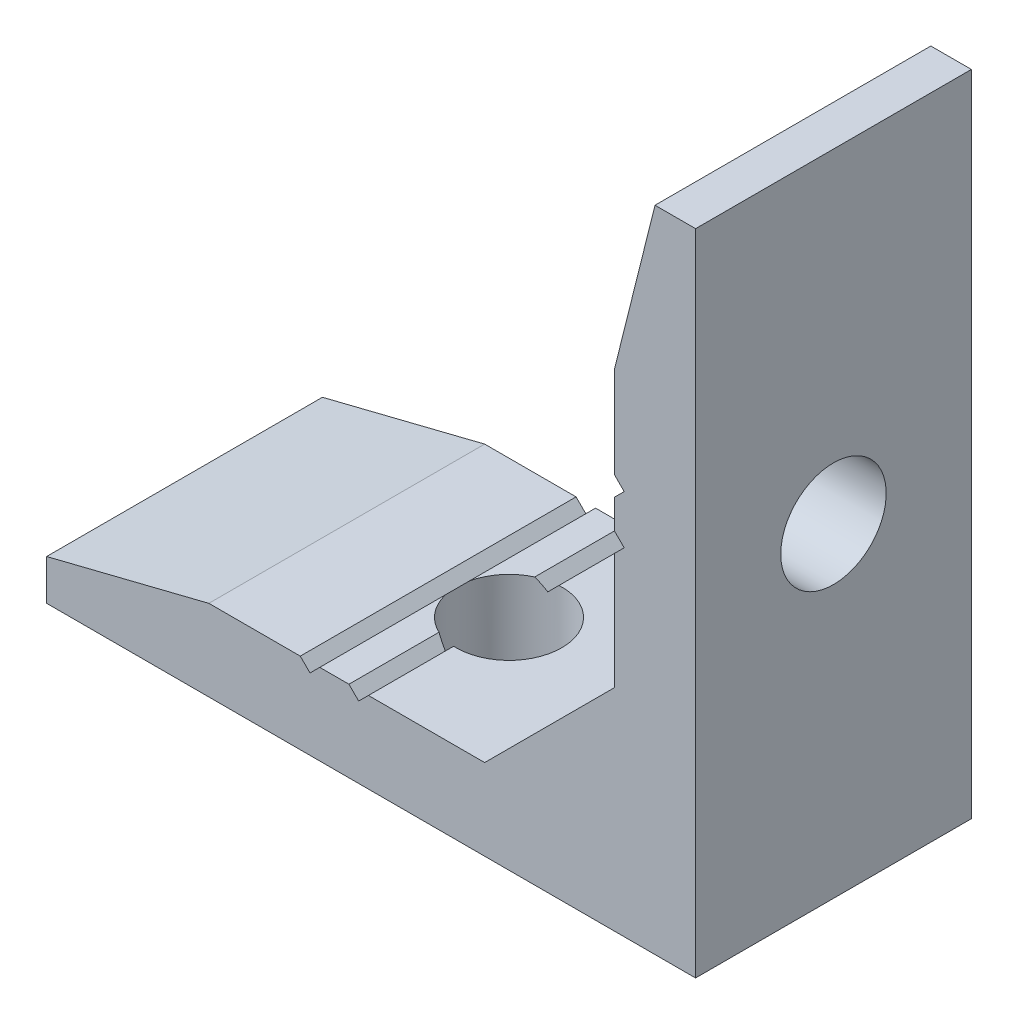
SolidWorks part; units mm, degrees
ref_plane "前视基准面" through (0, 0, 0) normal (0, 0, 1) x (1, 0, 0)
ref_plane "上视基准面" through (0, 0, 0) normal (0, 1, 0) x (1, 0, 0)
ref_plane "右视基准面" through (0, 0, 0) normal (1, 0, 0) x (0, 0, -1)
sketch "草图1" plane through (0, 0, 0) normal (0, 0, 1) x (1, 0, 0)
  line B0 (0, 0) -> (40, 0)
  line B1 (40, 0) -> (40, 40)
  line B2 (10, 5) -> (15.635, 5)
  line B3 (16.835, 5) -> (18.635, 5)
  line B4 (19.835, 5) -> (27, 5)
  line B5 (35, 13) -> (35, 20.165)
  line B6 (35, 21.365) -> (35, 23.165)
  line B7 (35, 24.365) -> (35, 30)
  line B8 (0, 2.5) -> (0, 0)
  line B9 (37.5, 40) -> (40, 40)
  line B10 (0, 2.5) -> (10, 5)
  line B11 (37.5, 40) -> (35, 30)
  line B12 (27, 5) -> (35, 13)
  line B13 (16.235, 4.4) -> (15.635, 5)
  line B14 (16.235, 4.4) -> (16.835, 5)
  line B15 (19.235, 4.4) -> (18.635, 5)
  line B16 (19.235, 4.4) -> (19.835, 5)
  line B17 (35.6, 23.765) -> (35, 24.365)
  line B18 (35.6, 23.765) -> (35, 23.165)
  line B19 (35.6, 20.765) -> (35, 21.365)
  line B20 (35.6, 20.765) -> (35, 20.165)
sketch_block_instance "A$C2EE5613F-1"
sketch_block "A$C2EE5613F"
extrude "凸台-拉伸1" add sketch "草图1" along normal mid plane 17
sketch "草图3" plane through (0, 5, 0) normal (0, 1, 0) x (1, 0, 0)
  line L0 (0, -8.5) -> (0, 8.5) construction
  circle A0 centre (20, 0) radius 3.25
  dimension "D1" = 20
extrude "切除-拉伸1" cut sketch "草图3" against normal through all
sketch "草图4" plane through (35, 0, 0) normal (-1, 0, 0) x (0, 0, 1)
  line L0 (8.5, 40) -> (-8.5, 40) construction
  circle A0 centre (0, 20) radius 3.25
  dimension "D1" = 6.5
  dimension "D2" = 20
extrude "切除-拉伸2" cut sketch "草图4" against normal through all
